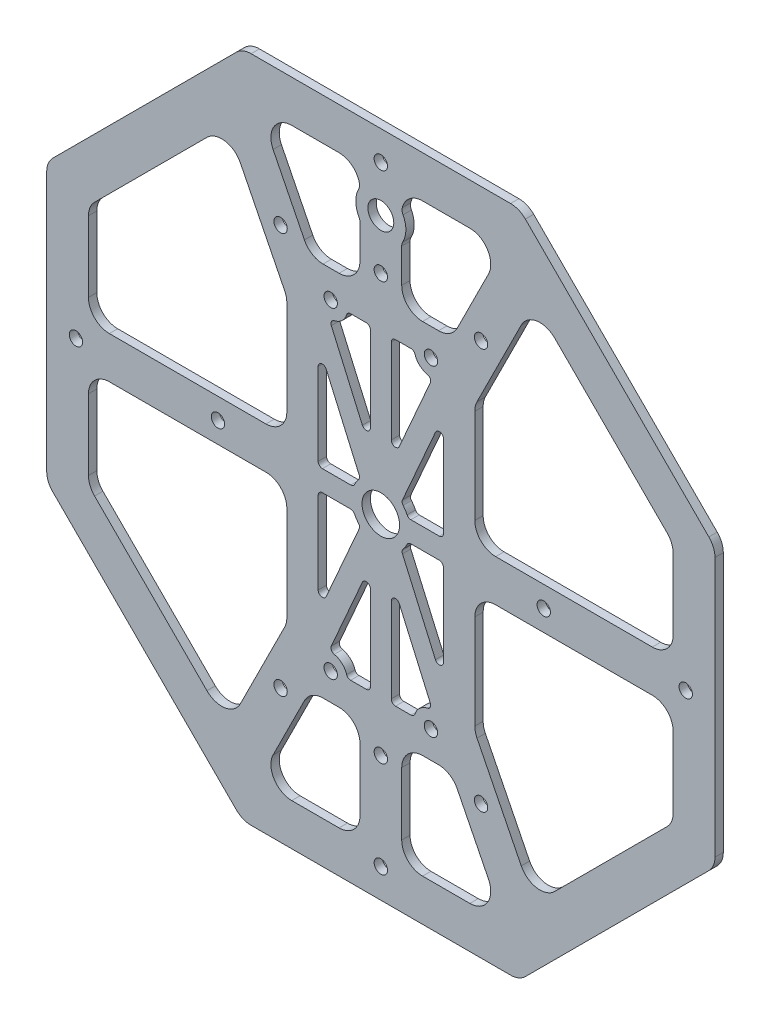
SolidWorks part; units mm, degrees
ref_plane "前视基准面" through (0, 0, 0) normal (0, 0, 1) x (1, 0, 0)
ref_plane "上视基准面" through (0, 0, 0) normal (0, 1, 0) x (1, 0, 0)
ref_plane "右视基准面" through (0, 0, 0) normal (1, 0, 0) x (0, 0, -1)
sketch "草图1" plane through (0, 0, 0) normal (0, 0, 1) x (1, 0, 0)
  line L1 (-80, 80) -> (80, 80)
  line L2 (-80, 80) -> (-80, -80)
  line L3 (-80, -80) -> (80, -80)
  line L4 (80, 80) -> (80, -80)
  line L5 (-80, 80) -> (80, -80) construction
  line L6 (-80, -80) -> (80, 80) construction
  point P0 (0, 0)
  dimension "D1" = 160
  dimension "D2" = 160
extrude "凸台-拉伸1" add sketch "草图1" along normal blind 2
sketch "草图2" plane through (0, 0, 2) normal (0, 0, 1) x (1, 0, 0)
  line L0 (0, 0) -> (73, 0) construction
  line L1 (-73, 73) -> (73, 73) construction
  line L2 (-73, 73) -> (-73, -73) construction
  line L3 (-73, -73) -> (73, -73) construction
  line L4 (73, 73) -> (73, -73) construction
  line L5 (-73, 73) -> (73, -73) construction
  line L6 (-73, -73) -> (73, 73) construction
  line L7 (0, 0) -> (0, 73) construction
  circle A0 centre (0, 0) radius 4.5
  circle A1 centre (-73, -73) radius 1.6 construction
  circle A2 centre (73, -73) radius 1.6 construction
  circle A3 centre (73, 73) radius 1.6 construction
  circle A4 centre (-73, 73) radius 1.6 construction
  circle A5 centre (-73, 0) radius 1.6
  circle A6 centre (0, -73) radius 1.6
  circle A7 centre (73, 0) radius 1.6
  circle A8 centre (0, 73) radius 1.6
  dimension "D1" = 9
  dimension "D4" = 3.2
  dimension "D5" = 3.2
  dimension "D6" = 3.2
  dimension "D7" = 3.2
  dimension "D2" = 146
  dimension "D3" = 146
extrude "切除-拉伸1" cut sketch "草图2" against normal blind 3
sketch "草图3" plane through (0, 0, 2) normal (0, 0, 1) x (1, 0, 0)
  line L0 (0, 0) -> (80, 0) construction
  line L1 (-33.1371, 80) -> (-80, 33.1371)
  line L2 (-80, 33.1371) -> (-80, -33.1371)
  line L3 (-80, -33.1371) -> (-33.1371, -80)
  line L4 (-33.1371, -80) -> (33.1371, -80)
  line L5 (33.1371, -80) -> (80, -33.1371)
  line L6 (80, -33.1371) -> (80, 33.1371)
  line L7 (80, 33.1371) -> (33.1371, 80)
  line L8 (33.1371, 80) -> (-33.1371, 80)
  line L9 (0, 0) -> (80, 0) construction
  line L10 (80, -80) -> (80, 80) construction
  line L12 (-100, 100) -> (100, 100)
  line L13 (-100, 100) -> (-100, -100)
  line L14 (-100, -100) -> (100, -100)
  line L15 (100, 100) -> (100, -100)
  line L16 (-100, 100) -> (100, -100) construction
  line L17 (-100, -100) -> (100, 100) construction
  circle A0 centre (0, 0) radius 80 construction
  dimension "D1" = 200
  dimension "D2" = 200
extrude "切除-拉伸2" cut sketch "草图3" against normal blind 10
sketch "草图5" plane through (0, 0, 2) normal (0, 0, 1) x (1, 0, 0)
  line L0 (-80, 0) -> (80, 0) construction
  line L1 (-22.5, 45) -> (22.5, 45) construction
  line L2 (-22.5, 45) -> (-22.5, -45) construction
  line L3 (-22.5, -45) -> (22.5, -45) construction
  line L4 (22.5, 45) -> (22.5, -45) construction
  line L5 (-22.5, 45) -> (22.5, -45) construction
  line L6 (-22.5, -45) -> (22.5, 45) construction
  line L7 (-80, 33.1371) -> (-80, -33.1371) construction
  line L8 (80, -33.1371) -> (80, 33.1371) construction
  line L9 (0, 80) -> (0, -80) construction
  line L10 (33.1371, 80) -> (-33.1371, 80) construction
  line L11 (-33.1371, -80) -> (33.1371, -80) construction
  line L18 (-70, -5) -> (-70, -28.9949)
  line L19 (-22.5, -5) -> (-70, -5)
  line L28 (-22.5, -45) -> (-37.7124, -75.4247) construction
  line L29 (-80, -33.1371) -> (-33.1371, -80) construction
  line L30 (-22.5, -33.8197) -> (-36.7251, -62.2699)
  line L31 (-70, -28.9949) -> (-36.7251, -62.2699)
  line L33 (-16.9098, -45) -> (-29.4098, -70)
  line L34 (-16.9098, -45) -> (-5, -45)
  line L35 (-5, -45) -> (-5, -70)
  line L36 (-5, -70) -> (-29.4098, -70)
  line L37 (-22.5, -5) -> (-22.5, -33.8197)
  line L38 (16.9098, -45) -> (5, -45)
  line L39 (5, -45) -> (5, -70)
  line L40 (5, -70) -> (29.4098, -70)
  line L41 (16.9098, -45) -> (29.4098, -70)
  line L42 (22.5, -5) -> (22.5, -33.8197)
  line L43 (22.5, -5) -> (70, -5)
  line L44 (70, -5) -> (70, -28.9949)
  line L45 (70, -28.9949) -> (36.7251, -62.2699)
  line L46 (22.5, -33.8197) -> (36.7251, -62.2699)
  line L47 (22.5, 5) -> (70, 5)
  line L48 (70, 5) -> (70, 28.9949)
  line L49 (70, 28.9949) -> (36.7251, 62.2699)
  line L50 (22.5, 33.8197) -> (36.7251, 62.2699)
  line L51 (22.5, 5) -> (22.5, 33.8197)
  line L52 (16.9098, 45) -> (29.4098, 70)
  line L53 (5, 70) -> (29.4098, 70)
  line L54 (5, 45) -> (5, 70)
  line L55 (16.9098, 45) -> (5, 45)
  line L56 (-16.9098, 45) -> (-5, 45)
  line L57 (-5, 45) -> (-5, 70)
  line L58 (-5, 70) -> (-29.4098, 70)
  line L59 (-16.9098, 45) -> (-29.4098, 70)
  line L60 (-22.5, 5) -> (-22.5, 33.8197)
  line L61 (-22.5, 5) -> (-70, 5)
  line L62 (-70, 5) -> (-70, 28.9949)
  line L63 (-70, 28.9949) -> (-36.7251, 62.2699)
  line L64 (-22.5, 33.8197) -> (-36.7251, 62.2699)
  point P0 (0, 0)
  dimension "D1" = 45
  dimension "D2" = 90
  dimension "D3" = 5
  dimension "D4" = 10
  dimension "D6" = 10
  dimension "D7" = 10
  dimension "D8" = 5
  dimension "D9" = 5
  dimension "D10" = 10
extrude "切除-拉伸3" cut sketch "草图5" against normal blind 10
sketch "草图6" plane through (0, 0, 2) normal (0, 0, 1) x (1, 0, 0)
  line L0 (0, -38.5) -> (0, 38.5) construction
  line L1 (-12, 38.5) -> (12, 38.5) construction
  line L2 (-12, 38.5) -> (-12, -38.5) construction
  line L3 (-12, -38.5) -> (12, -38.5) construction
  line L4 (12, 38.5) -> (12, -38.5) construction
  line L5 (-12, 38.5) -> (12, -38.5) construction
  line L6 (-12, -38.5) -> (12, 38.5) construction
  circle A0 centre (-12, 38.5) radius 1.6
  circle A1 centre (-12, -38.5) radius 1.6
  circle A2 centre (12, -38.5) radius 1.6
  circle A3 centre (12, 38.5) radius 1.6
  point P0 (0, 0)
  dimension "D3" = 3.2
  dimension "D4" = 3.2
  dimension "D1" = 24
  dimension "D2" = 77
extrude "切除-拉伸4" cut sketch "草图6" against normal blind 10
fillet "圆角1" radius 5 8 edges at (33.1371, 80, 1) (-33.1371, 80, 1) (-80, 33.1371, 1) (-33.1371, -80, 1) (33.1371, -80, 1) (80, -33.1371, 1) (80, 33.1371, 1) (-80, -33.1371, 1)
fillet "圆角2" radius 5 36 edges at (5, -70, 1) (5, -45, 1) (16.9098, -45, 1) (29.4098, -70, 1) (-5, -70, 1) (-29.4098, -70, 1) (-16.9098, -45, 1) (-5, -45, 1) (-5, 70, 1) (-5, 45, 1) (-16.9098, 45, 1) (-29.4098, 70, 1) (-70, 28.9949, 1) (-36.7251, 62.2699, 1) (-22.5, 33.8197, 1) (-22.5, 5, 1) (-70, 5, 1) (36.7251, 62.2699, 1) (70, 28.9949, 1) (70, 5, 1) (22.5, 5, 1) (22.5, 33.8197, 1) (5, 70, 1) (29.4098, 70, 1) (16.9098, 45, 1) (5, 45, 1) (70, -28.9949, 1) (36.7251, -62.2699, 1) (22.5, -33.8197, 1) (22.5, -5, 1) (70, -5, 1) (-36.7251, -62.2699, 1) (-70, -5, 1) (-22.5, -5, 1) (-22.5, -33.8197, 1) (-70, -28.9949, 1)
sketch "草图7" plane through (0, 0, 2) normal (0, 0, 1) x (1, 0, 0)
  line L0 (-18, 0) -> (18, 0) construction
  line L1 (-18, 41) -> (18, 41) construction
  line L2 (-18, 41) -> (-18, -41) construction
  line L3 (-18, -41) -> (18, -41) construction
  line L4 (18, 41) -> (18, -41) construction
  line L5 (-18, 41) -> (18, -41) construction
  line L6 (-18, -41) -> (18, 41) construction
  line L7 (0, 41) -> (0, -41) construction
  line L8 (-15, -2.5) -> (-15, -27.9476)
  line L9 (-15, -27.9476) -> (-4.9175, -4.9818)
  line L10 (-15, -2.5) -> (-6.5383, -2.5)
  line L11 (-2.5, -11.9135) -> (-12.426, -34.5228)
  line L12 (-8.0314, -38) -> (-2.5, -38)
  line L13 (-2.5, -38) -> (-2.5, -11.9135)
  line L14 (2.5, -11.9135) -> (12.426, -34.5228)
  line L15 (2.5, -38) -> (2.5, -11.9135)
  line L16 (8.0314, -38) -> (2.5, -38)
  line L17 (15, -2.5) -> (6.5383, -2.5)
  line L18 (15, -2.5) -> (15, -27.9476)
  line L19 (15, -27.9476) -> (4.9175, -4.9818)
  line L20 (15, 2.5) -> (15, 27.9476)
  line L21 (15, 27.9476) -> (4.9175, 4.9818)
  line L22 (15, 2.5) -> (6.5383, 2.5)
  line L23 (8.0314, 38) -> (2.5, 38)
  line L24 (2.5, 38) -> (2.5, 11.9135)
  line L25 (2.5, 11.9135) -> (12.426, 34.5228)
  line L26 (-2.5, 11.9135) -> (-12.426, 34.5228)
  line L27 (-2.5, 38) -> (-2.5, 11.9135)
  line L28 (-8.0314, 38) -> (-2.5, 38)
  line L29 (-15, 2.5) -> (-6.5383, 2.5)
  line L30 (-15, 2.5) -> (-15, 27.9476)
  line L31 (-15, 27.9476) -> (-4.9175, 4.9818)
  arc A0 (-6.5383, -2.5) -> (-4.9175, -4.9818) centre (0, 0) ccw
  arc A1 (-8.0314, -38) -> (-12.426, -34.5228) centre (-12, -38.5) ccw
  arc A2 (8.0314, -38) -> (12.426, -34.5228) centre (12, -38.5) cw
  arc A3 (6.5383, -2.5) -> (4.9175, -4.9818) centre (0, 0) cw
  arc A4 (6.5383, 2.5) -> (4.9175, 4.9818) centre (0, 0) ccw
  arc A5 (8.0314, 38) -> (12.426, 34.5228) centre (12, 38.5) ccw
  arc A6 (-8.0314, 38) -> (-12.426, 34.5228) centre (-12, 38.5) cw
  arc A7 (-6.5383, 2.5) -> (-4.9175, 4.9818) centre (0, 0) cw
  point P0 (0, 0)
  dimension "D3" = 14
  dimension "D8" = 8
  dimension "D1" = 82
  dimension "D2" = 36
  dimension "D4" = 5
  dimension "D5" = 3
  dimension "D6" = 2.5
  dimension "D7" = 5
  dimension "D9" = 2.5
  dimension "D10" = 3
extrude "切除-拉伸5" cut sketch "草图7" against normal blind 10
fillet "圆角3" radius 1 32 edges at (-4.9175, -4.9818, 1) (-15, -27.9476, 1) (-15, -2.5, 1) (-6.5383, -2.5, 1) (2.5, 11.9135, 1) (2.5, 38, 1) (8.0314, 38, 1) (12.426, 34.5228, 1) (-2.5, 38, 1) (-2.5, 11.9135, 1) (-12.426, 34.5228, 1) (-8.0314, 38, 1) (-4.9175, 4.9818, 1) (-6.5383, 2.5, 1) (-15, 2.5, 1) (2.5, -38, 1) (2.5, -11.9135, 1) (12.426, -34.5228, 1) (8.0314, -38, 1) (-2.5, -11.9135, 1) (-2.5, -38, 1) (-8.0314, -38, 1) (-12.426, -34.5228, 1) (4.9175, -4.9818, 1) (6.5383, -2.5, 1) (15, -2.5, 1) (15, -27.9476, 1) (4.9175, 4.9818, 1) (15, 27.9476, 1) (15, 2.5, 1) (6.5383, 2.5, 1) (-15, 27.9476, 1)
sketch "草图8" plane through (0, 0, 2) normal (0, 0, 1) x (1, 0, 0)
  line L0 (0, -50) -> (0, 0) construction
  line L1 (-39, 50) -> (39, 50) construction
  line L2 (-39, 50) -> (-39, -50) construction
  line L3 (-39, -50) -> (39, -50) construction
  line L4 (39, 50) -> (39, -50) construction
  line L5 (-39, 50) -> (39, -50) construction
  line L6 (-39, -50) -> (39, 50) construction
  line L7 (0, 0) -> (-39, 0) construction
  circle A0 centre (-39, 0) radius 1.6
  circle A1 centre (0, -50) radius 1.6
  circle A2 centre (39, 0) radius 1.6
  circle A3 centre (0, 50) radius 1.6
  point P0 (0, 0)
  dimension "D3" = 3.2
  dimension "D4" = 3.2
  dimension "D1" = 78
  dimension "D2" = 100
extrude "切除-拉伸6" cut sketch "草图8" against normal blind 10
sketch "草图9" plane through (0, 0, 2) normal (0, 0, 1) x (1, 0, 0)
  line L0 (0, 0) -> (-24, 0) construction
  line L1 (-24, 48) -> (24, 48) construction
  line L2 (-24, 48) -> (-24, -48) construction
  line L3 (-24, -48) -> (24, -48) construction
  line L4 (24, 48) -> (24, -48) construction
  line L5 (-24, 48) -> (24, -48) construction
  line L6 (-24, -48) -> (24, 48) construction
  circle A0 centre (-24, -48) radius 1.6
  circle A1 centre (24, -48) radius 1.6
  circle A2 centre (24, 48) radius 1.6
  circle A3 centre (-24, 48) radius 1.6
  point P0 (0, 0)
  dimension "D3" = 3.2
  dimension "D4" = 3.2
  dimension "D1" = 48
  dimension "D2" = 96
extrude "切除-拉伸7" cut sketch "草图9" against normal blind 10
sketch "草图10" plane through (0, 0, 2) normal (0, 0, 1) x (1, 0, 0)
  line L0 (0, 0) -> (0, -80) construction
  line L1 (-31.066, -80) -> (31.066, -80) construction
  line L2 (0, 0) -> (0, 80) construction
  line L3 (31.066, 80) -> (-31.066, 80) construction
  circle A1 centre (0, 62) radius 3.1
  dimension "D1" = 6.2
  dimension "D2" = 62
extrude "切除-拉伸8" cut sketch "草图10" against normal blind 10
sketch "草图11" plane through (0, 0, 2) normal (0, 0, 1) x (1, 0, 0)
  circle A0 centre (0, 62) radius 3.1
  circle A1 centre (0, 62) radius 6
  dimension "D1" = 6.2
  dimension "D2" = 12
extrude "凸台-拉伸2" add sketch "草图11" against normal blind 2
fillet "圆角4" radius 2 4 edges at (5.0092, 65.3028, 1) (-5, 58.6834, 1) (-5.0092, 65.3028, 1) (5, 58.6834, 1)
